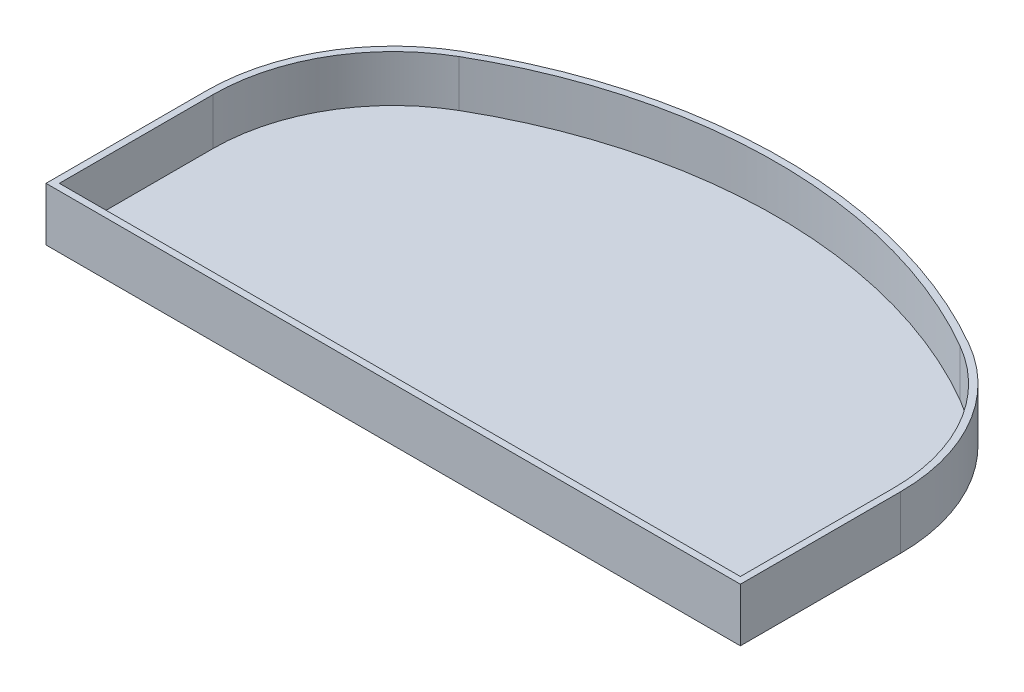
SolidWorks part; units mm, degrees
ref_plane "Front Plane" through (0, 0, 0) normal (0, 0, 1) x (1, 0, 0)
ref_plane "Top Plane" through (0, 0, 0) normal (0, 1, 0) x (1, 0, 0)
ref_plane "Right Plane" through (0, 0, 0) normal (1, 0, 0) x (0, 0, -1)
sketch "Sketch1" plane through (0, 0, 0) normal (0, 1, 0) x (1, 0, 0)
  line L5 (0, 0) -> (330.2, 0)
  line L6 (0, 0) -> (0, 76.2)
  line L10 (330.2, 76.2) -> (330.2, 0)
  line L11 (44.45, 153.1897) -> (-66.4365, 89.1693) construction
  line L12 (165.1, 0) -> (165.1, -55.7823) construction
  arc A0 (0, 76.2) -> (44.45, 153.1897) centre (88.9, 76.2) cw
  arc A1 (44.45, 153.1897) -> (285.75, 153.1897) centre (165.1, -55.7823) cw
  arc A2 (285.75, 153.1897) -> (330.2, 76.2) centre (241.3, 76.2) cw
  circle A3 centre (88.9, 76.2) radius 63.5 construction
  circle A4 centre (241.3, 76.2) radius 63.5 construction
  point P10 (165.1, 185.5177)
  dimension "D4" = 88.9
  dimension "D6" = 127
  dimension "D1" = 330.2
  dimension "D2" = 76.2
  dimension "D3" = 30
  dimension "D5" = 185.5177
extrude "Boss-Extrude1" add sketch "Sketch1" along normal blind 25.4
shell "Shell1" thickness 3.175
